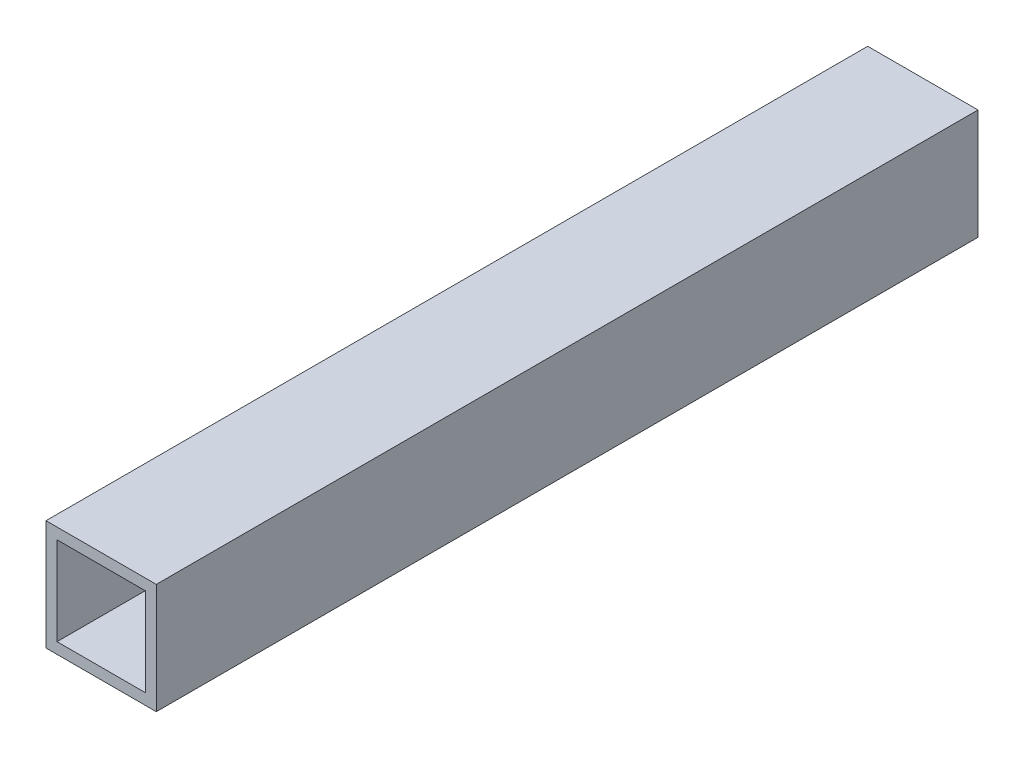
SolidWorks part; units mm, degrees
material "Д16Т ГОСТ 4784-74"
ref_plane "Спереди" through (0, 0, 0) normal (0, 0, 1) x (1, 0, 0)
ref_plane "Сверху" through (0, 0, 0) normal (0, 1, 0) x (1, 0, 0)
ref_plane "Справа" through (0, 0, 0) normal (1, 0, 0) x (0, 0, -1)
sketch "Эскиз1" plane through (0, 0, 0) normal (0, 0, 1) x (1, 0, 0)
  line L1 (0, 0) -> (40, 0)
  line L2 (0, 0) -> (0, 40)
  line L3 (0, 40) -> (40, 40)
  line L4 (40, 0) -> (40, 40)
  dimension "D1" = 40
  dimension "D2" = 40
extrude "Вытянуть-Тонкостенный1" add sketch "Эскиз1" along normal blind 298 thin thin type one direction reverse wall 4
